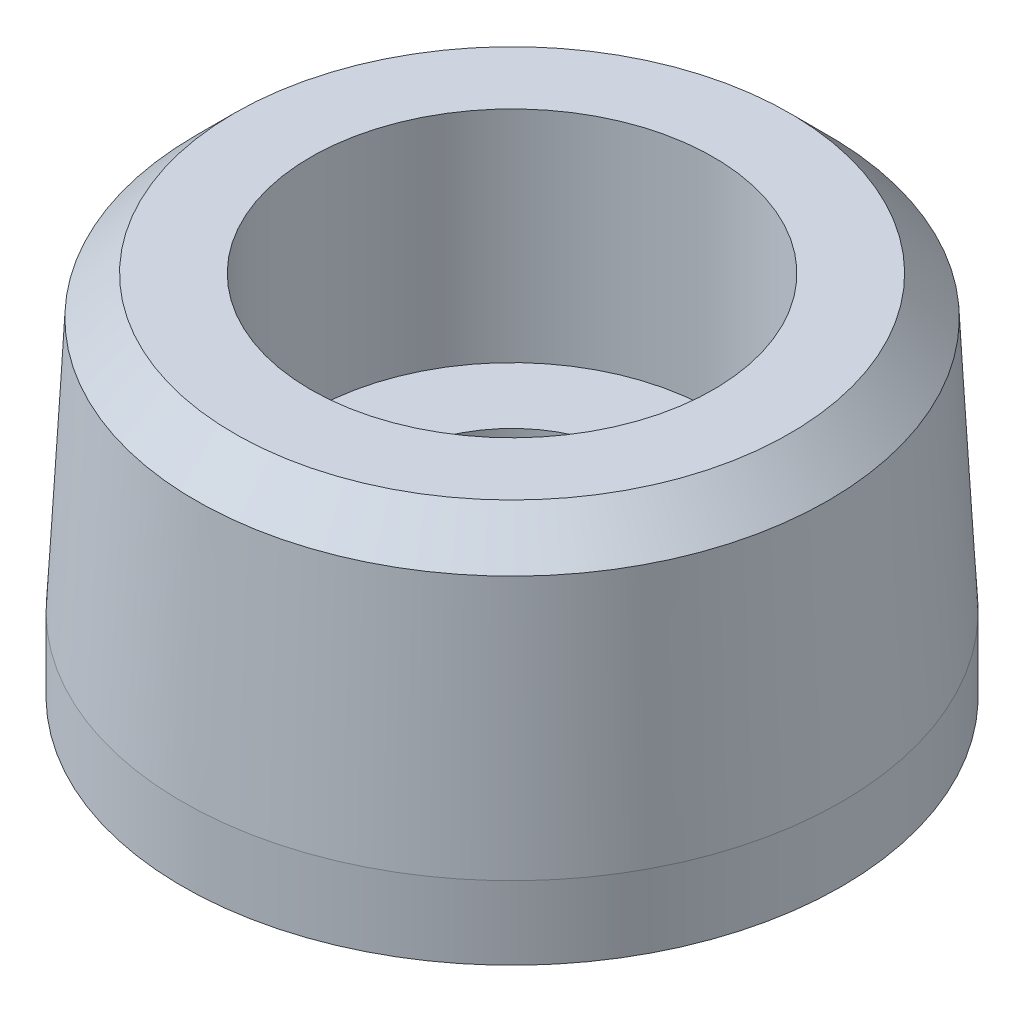
SolidWorks part; units mm, degrees
material "POM"
ref_plane "前视" through (0, 0, 0) normal (0, 0, 1) x (1, 0, 0)
ref_plane "上视" through (0, 0, 0) normal (0, 1, 0) x (1, 0, 0)
ref_plane "右视" through (0, 0, 0) normal (1, 0, 0) x (0, 0, -1)
sketch "草图1" plane through (0, 0, 0) normal (0, 0, 1) x (1, 0, 0)
  line L0 (0, -1000) -> (0, 49000) construction
  line L1 (0, 0) -> (9, 0)
  line L2 (9, 0) -> (9, 2)
  line L3 (9, 2) -> (8.5807, 10)
  line L4 (8.5807, 10) -> (0, 10)
  line L5 (0, 10) -> (0, 0)
  dimension "D1" = 18
  dimension "D2" = 3
  dimension "D3" = 2
  dimension "D4" = 10
revolve "旋转1" add sketch "草图1" angle 360 about L0
hole_wizard "打孔尺寸根据内六角圆柱头螺钉的类型1" positions "草图3" profile "草图2" counterbore size "M6" standard "Gb" end condition through all
sketch "草图3" plane through (0, 10, 0) normal (0, 1, 0) x (1, 0, 0)
  point P0 (0, 0)
sketch "草图2" plane through (0, 10, 0) normal (1, 0, 0) x (0, 0, 1)
  line L0 (0, 0) -> (0, 10)
  line L1 (0, 10) -> (3.3, 10)
  line L3 (3.3, 10) -> (3.3, 6)
  line L4 (3.3, 6) -> (5.5, 6)
  line L5 (5.5, 6) -> (5.5, 0)
  line L7 (5.5, 0) -> (0, 0)
  line L11 (0, -6.35) -> (0, 107.95) construction
  dimension "通孔孔直径" = 6.6
  dimension "通孔孔深度" = 10
  dimension "柱形沉头孔直径" = 11
  dimension "柱形沉头孔深度" = 6
chamfer "倒角1" distance 1 angle 45 1 edges at (8.5807, 10, 0)
